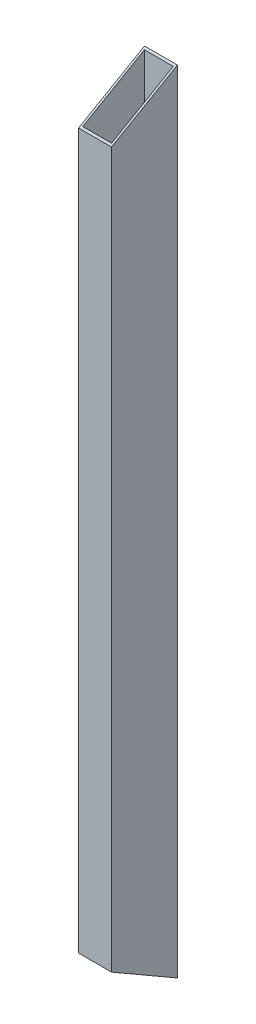
SolidWorks part; units mm, degrees
ref_plane "Front Plane" through (0, 0, 0) normal (0, 0, 1) x (1, 0, 0)
ref_plane "Top Plane" through (0, 0, 0) normal (0, 1, 0) x (1, 0, 0)
ref_plane "Right Plane" through (0, 0, 0) normal (1, 0, 0) x (0, 0, -1)
sketch "Sketch1" plane through (0, 0, 0) normal (0, 1, 0) x (1, 0, 0)
  line L1 (12.7, -25.4) -> (-12.7, -25.4)
  line L2 (12.7, -25.4) -> (12.7, 25.4)
  line L3 (12.7, 25.4) -> (-12.7, 25.4)
  line L4 (-12.7, -25.4) -> (-12.7, 25.4)
  line L5 (12.7, -25.4) -> (-12.7, 25.4) construction
  line L6 (12.7, 25.4) -> (-12.7, -25.4) construction
  line L7 (11.1125, -23.8125) -> (-11.1125, -23.8125)
  line L8 (11.1125, -23.8125) -> (11.1125, 23.8125)
  line L9 (11.1125, 23.8125) -> (-11.1125, 23.8125)
  line L10 (-11.1125, -23.8125) -> (-11.1125, 23.8125)
  line L11 (11.1125, -23.8125) -> (-11.1125, 23.8125) construction
  line L12 (11.1125, 23.8125) -> (-11.1125, -23.8125) construction
  point P0 (0, 0)
  point P6 (0, 0)
  dimension "D1" = 50.8
  dimension "D2" = 25.4
  dimension "D3" = 47.625
  dimension "D4" = 22.225
extrude "Boss-Extrude1" add sketch "Sketch1" along normal blind 609.6
sketch "Sketch2" plane through (12.7, 0, 0) normal (1, 0, 0) x (0, 0, -1)
  line L0 (25.4, 609.6) -> (-25.4, 609.6)
  line L1 (-25.4, 609.6) -> (-25.4, 580.2706)
  line L2 (-25.4, 609.6) -> (-25.4, 0) construction
  line L3 (-25.4, 580.2706) -> (25.4, 609.6)
  dimension "D1" = 30
extrude "Cut-Extrude1" cut sketch "Sketch2" against normal through all
sketch "Sketch3" plane through (0, 0, 0) normal (1, 0, 0) x (0, 0, -1)
  line L0 (-25.4, 0) -> (25.4, 0)
  line L1 (25.4, 0) -> (-25.4, 29.3294)
  line L2 (-25.4, 580.2706) -> (-25.4, 0) construction
  line L3 (-25.4, 29.3294) -> (-25.4, 0)
  dimension "D1" = 30
extrude "Cut-Extrude2" cut sketch "Sketch3" against normal through all both and the other way through all contours L3 L0 L1
